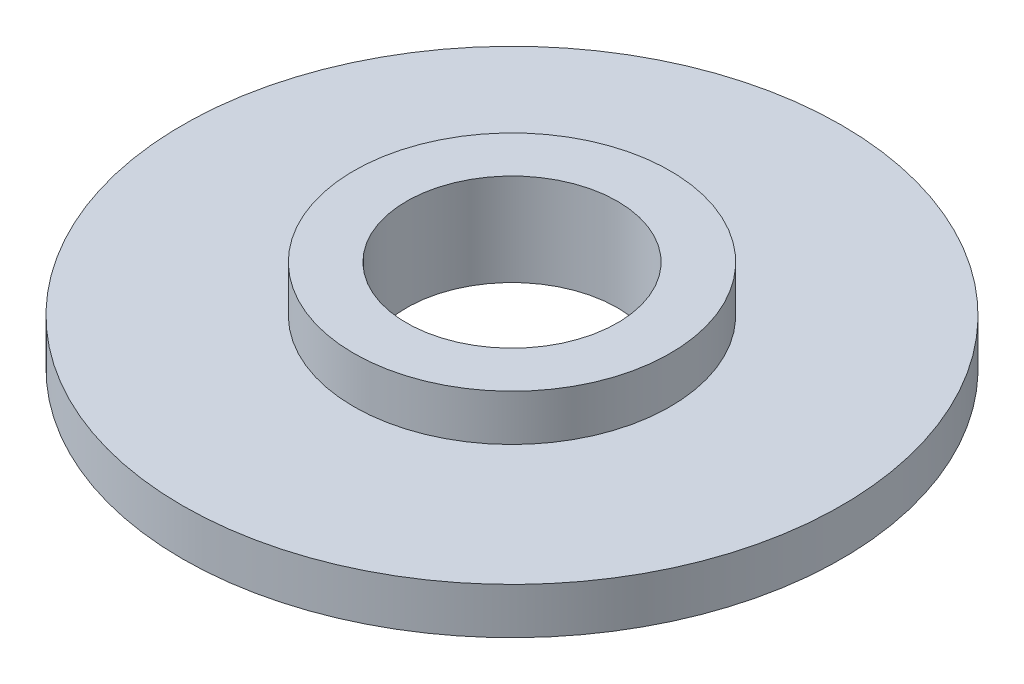
SolidWorks part; units mm, degrees
material "6061 Alloy"
ref_plane "Front Plane" through (0, 0, 0) normal (0, 0, 1) x (1, 0, 0)
ref_plane "Top Plane" through (0, 0, 0) normal (0, 1, 0) x (1, 0, 0)
ref_plane "Right Plane" through (0, 0, 0) normal (1, 0, 0) x (0, 0, -1)
sketch "Sketch1" plane through (0, 0, 0) normal (0, 1, 0) x (1, 0, 0)
  circle A0 centre (0, 0) radius 12.5
  circle A1 centre (0, 0) radius 4
  dimension "D1" = 25
  dimension "D2" = 8
extrude "Boss-Extrude1" add sketch "Sketch1" along normal blind 3.5
sketch "Sketch3" plane through (0, 3.5, 0) normal (0, 1, 0) x (1, 0, 0)
  circle A0 centre (0, 0) radius 6
  circle A1 centre (0, 0) radius 12.5
extrude "Cut-Extrude1" cut sketch "Sketch3" against normal blind 1.75
